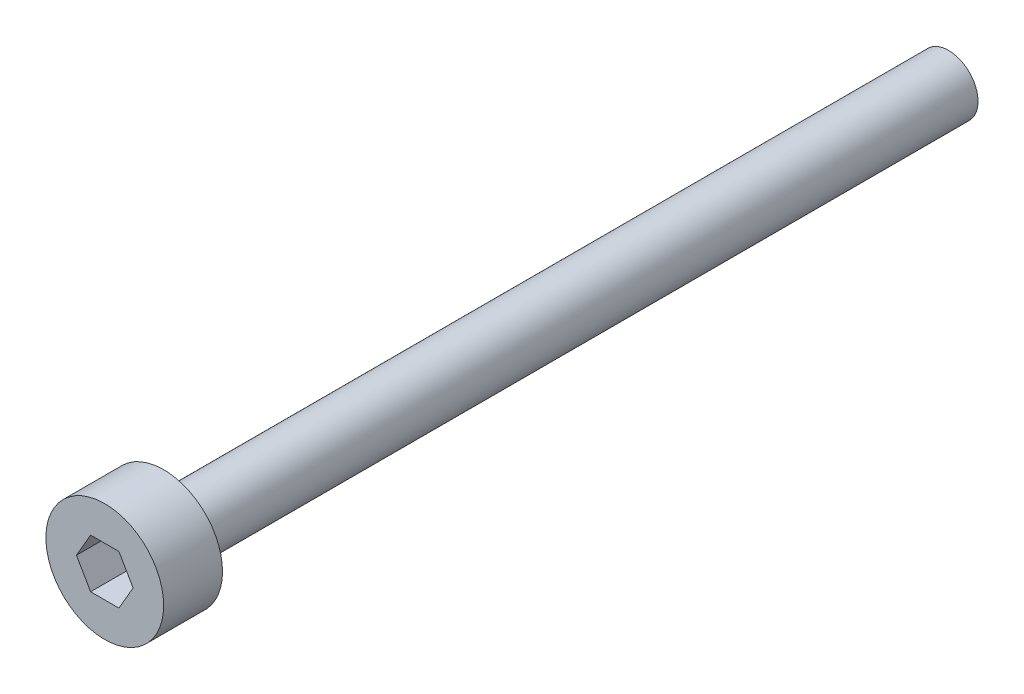
SolidWorks part; units mm, degrees
ref_plane "正面" through (0, 0, 0) normal (0, 0, 1) x (1, 0, 0)
ref_plane "平面" through (0, 0, 0) normal (0, 1, 0) x (1, 0, 0)
ref_plane "右側面" through (0, 0, 0) normal (1, 0, 0) x (0, 0, -1)
sketch "ｽｹｯﾁ5" plane through (0, 0, 0) normal (0, 0, 1) x (1, 0, 0)
  circle A0 centre (0, 0) radius 3
  dimension "D1" = 6
extrude "ﾎﾞｽ - 押し出し1" add sketch "ｽｹｯﾁ5" along normal blind 3
sketch "ｽｹｯﾁ6" plane through (0, 0, 3) normal (0, 0, 1) x (1, 0, 0)
  line L1 (1.4434, 0) -> (0.7217, 1.25)
  line L2 (0.7217, 1.25) -> (-0.7217, 1.25)
  line L3 (-0.7217, 1.25) -> (-1.4434, 0)
  line L4 (-1.4434, 0) -> (-0.7217, -1.25)
  line L5 (-0.7217, -1.25) -> (0.7217, -1.25)
  line L6 (0.7217, -1.25) -> (1.4434, 0)
  circle A0 centre (0, 0) radius 1.25 construction
  dimension "D1" = 2.5
extrude "ｶｯﾄ - 押し出し1" cut sketch "ｽｹｯﾁ6" against normal blind 2
sketch "ｽｹｯﾁ7" plane through (0, 0, 0) normal (0, 0, -1) x (-1, 0, 0)
  circle A0 centre (0, 0) radius 1.5
  dimension "D1" = 3
extrude "ﾎﾞｽ - 押し出し2" add sketch "ｽｹｯﾁ7" along normal blind 40
